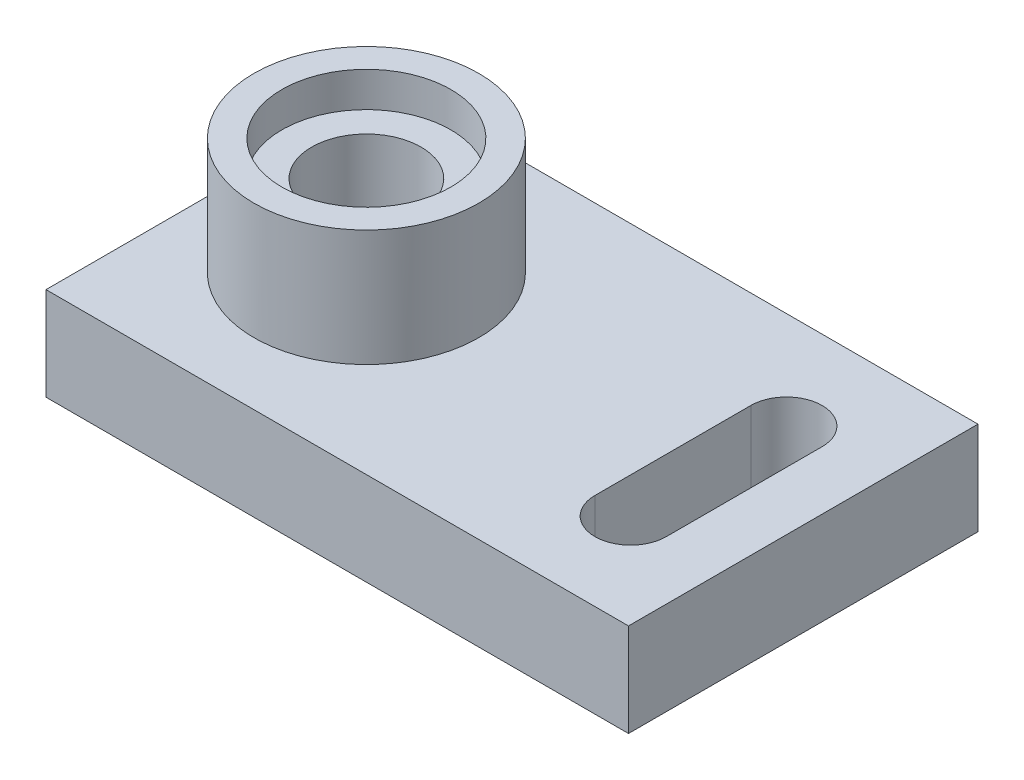
SolidWorks part; units mm, degrees
ref_plane "Front Plane" through (0, 0, 0) normal (0, 0, 1) x (1, 0, 0)
ref_plane "Top Plane" through (0, 0, 0) normal (0, 1, 0) x (1, 0, 0)
ref_plane "Right Plane" through (0, 0, 0) normal (1, 0, 0) x (0, 0, -1)
sketch "Sketch1" plane through (0, 0, 0) normal (0, 1, 0) x (1, 0, 0)
  line L0 (0, 0) -> (0, 76.2)
  line L1 (0, 76.2) -> (127, 76.2)
  line L2 (127, 76.2) -> (127, 0)
  line L3 (127, 0) -> (0, 0)
  dimension "D1" = 127
  dimension "D2" = 76.2
extrude "Boss-Extrude1" add sketch "Sketch1" along normal blind 20.32 contours L3 L0 L1 L2
sketch "Sketch2" plane through (0, 20.32, 0) normal (0, 1, 0) x (1, 0, 0)
  line L5 (106.4866, 20.9736) -> (106.4866, 54.9535) construction
  line L6 (98.7081, 20.9736) -> (98.7081, 54.9535)
  line L7 (114.2652, 20.9736) -> (114.2652, 54.9535)
  arc A0 (98.7081, 20.9736) -> (114.2652, 20.9736) centre (106.4866, 20.9736) ccw
  arc A1 (114.2652, 54.9535) -> (98.7081, 54.9535) centre (106.4866, 54.9535) ccw
  point P0 (0, 0)
  point P12 (106.4866, 37.9635)
extrude "Cut-Extrude2" cut sketch "Sketch2" against normal through all
sketch "Sketch4" plane through (0, 20.32, 0) normal (0, 1, 0) x (1, 0, 0)
  circle A0 centre (31.75, 38.1) radius 24.5151
extrude "Boss-Extrude2" add sketch "Sketch4" along normal blind 25.4
sketch "Sketch5" plane through (0, 45.72, 0) normal (0, 1, 0) x (1, 0, 0)
  circle A2 centre (31.75, 38.1) radius 17.9406
  circle A3 centre (31.75, 38.1) radius 11.9314
extrude "Cut-Extrude3" cut sketch "Sketch5" against normal through all contours A3
sketch "Sketch6" plane through (0, 45.72, 0) normal (0, 1, 0) x (1, 0, 0)
  circle A2 centre (31.75, 38.1) radius 18.4306
extrude "Cut-Extrude4" cut sketch "Sketch6" against normal blind 7.62
